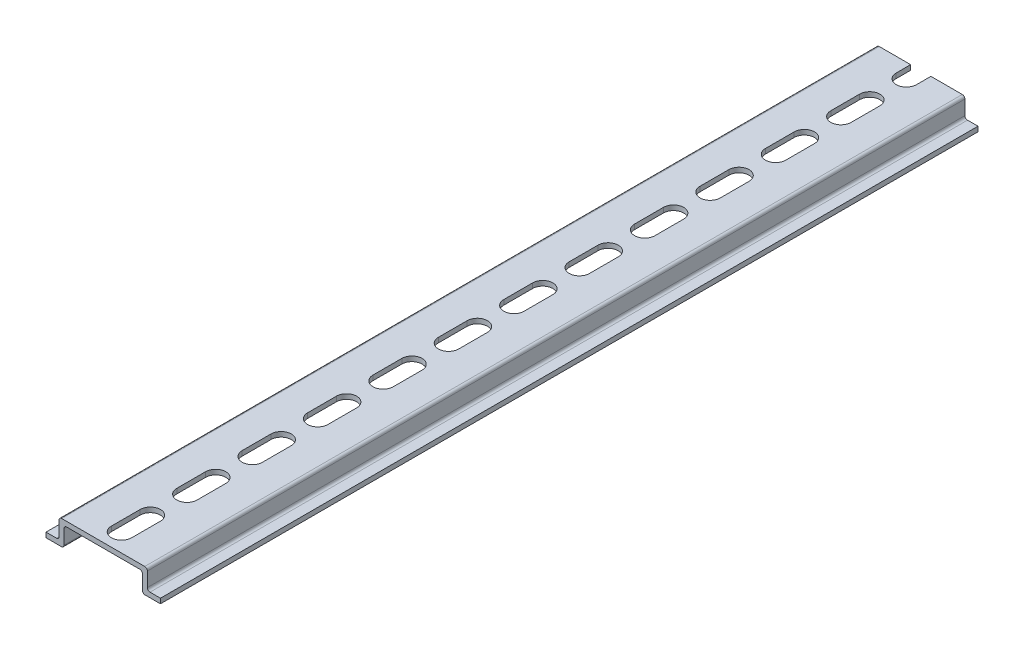
SolidWorks part; units mm, degrees
ref_plane "前视基准面" through (0, 0, 0) normal (0, 0, 1) x (1, 0, 0)
ref_plane "上视基准面" through (0, 0, 0) normal (0, 1, 0) x (1, 0, 0)
ref_plane "右视基准面" through (0, 0, 0) normal (1, 0, 0) x (0, 0, -1)
sketch "草图1" plane through (0, 0, 0) normal (0, 0, 1) x (1, 0, 0)
  line L0 (-17.5, 0) -> (-12.8, 0)
  line L1 (-12, 0.8) -> (-12, 5.2)
  line L2 (-11.2, 6) -> (11.2, 6)
  line L3 (12, 5.2) -> (12, 0.8)
  line L4 (12.8, 0) -> (17.5, 0)
  line L5 (13.5, 6.7) -> (13.5, 2.3)
  line L6 (12.7, 7.5) -> (-12.7, 7.5)
  line L7 (-13.5, 6.7) -> (-13.5, 2.3)
  line L8 (-14.3, 1.5) -> (-17.5, 1.5)
  line L9 (14.3, 1.5) -> (17.5, 1.5)
  line L10 (17.5, 1.5) -> (17.5, 0)
  line L11 (-17.5, 0) -> (-17.5, 1.5)
  line L12 (0, -9.8538) -> (0, 21.8077) construction
  arc A0 (12.7, 7.5) -> (13.5, 6.7) centre (12.7, 6.7) cw
  arc A1 (14.3, 1.5) -> (13.5, 2.3) centre (14.3, 2.3) cw
  arc A2 (12.8, 0) -> (12, 0.8) centre (12.8, 0.8) cw
  arc A3 (12, 5.2) -> (11.2, 6) centre (11.2, 5.2) ccw
  arc A4 (-12.8, 0) -> (-12, 0.8) centre (-12.8, 0.8) ccw
  arc A5 (-11.2, 6) -> (-12, 5.2) centre (-11.2, 5.2) ccw
  arc A6 (-13.5, 6.7) -> (-12.7, 7.5) centre (-12.7, 6.7) cw
  arc A7 (-13.5, 2.3) -> (-14.3, 1.5) centre (-14.3, 2.3) cw
  dimension "D6" = 0.8
  dimension "D1" = 1.5
  dimension "D2" = 7.5
  dimension "D3" = 35
  dimension "D4" = 1.5
  dimension "D5" = 1.5
  dimension "D7" = 27
extrude "凸台-拉伸1" add sketch "草图1" along normal blind 250
sketch "草图2" plane through (0, 0, 0) normal (0, 1, 0) x (1, 0, 0)
  line L0 (0, 22.1231) -> (0, -285.8608) construction
  line L1 (0, 4.4) -> (0, -4.4) construction
  line L2 (3.1, 4.4) -> (3.1, -4.4)
  line L3 (-3.1, 4.4) -> (-3.1, -4.4)
  line L4 (0, -15.6) -> (0, -24.4) construction
  line L5 (3.1, -15.6) -> (3.1, -24.4)
  line L6 (-3.1, -15.6) -> (-3.1, -24.4)
  line L7 (0, -35.6) -> (0, -44.4) construction
  line L8 (3.1, -35.6) -> (3.1, -44.4)
  line L9 (-3.1, -35.6) -> (-3.1, -44.4)
  line L10 (0, -55.6) -> (0, -64.4) construction
  line L11 (3.1, -55.6) -> (3.1, -64.4)
  line L12 (-3.1, -55.6) -> (-3.1, -64.4)
  line L13 (0, -75.6) -> (0, -84.4) construction
  line L14 (3.1, -75.6) -> (3.1, -84.4)
  line L15 (-3.1, -75.6) -> (-3.1, -84.4)
  line L16 (0, -95.6) -> (0, -104.4) construction
  line L17 (3.1, -95.6) -> (3.1, -104.4)
  line L18 (-3.1, -95.6) -> (-3.1, -104.4)
  line L19 (0, -115.6) -> (0, -124.4) construction
  line L20 (3.1, -115.6) -> (3.1, -124.4)
  line L21 (-3.1, -115.6) -> (-3.1, -124.4)
  line L22 (0, -135.6) -> (0, -144.4) construction
  line L23 (3.1, -135.6) -> (3.1, -144.4)
  line L24 (-3.1, -135.6) -> (-3.1, -144.4)
  line L25 (0, -155.6) -> (0, -164.4) construction
  line L26 (3.1, -155.6) -> (3.1, -164.4)
  line L27 (-3.1, -155.6) -> (-3.1, -164.4)
  line L28 (0, -175.6) -> (0, -184.4) construction
  line L29 (3.1, -175.6) -> (3.1, -184.4)
  line L30 (-3.1, -175.6) -> (-3.1, -184.4)
  line L31 (0, -195.6) -> (0, -204.4) construction
  line L32 (3.1, -195.6) -> (3.1, -204.4)
  line L33 (-3.1, -195.6) -> (-3.1, -204.4)
  line L34 (0, -215.6) -> (0, -224.4) construction
  line L35 (3.1, -215.6) -> (3.1, -224.4)
  line L36 (-3.1, -215.6) -> (-3.1, -224.4)
  line L37 (0, -235.6) -> (0, -244.4) construction
  line L38 (3.1, -235.6) -> (3.1, -244.4)
  line L39 (-3.1, -235.6) -> (-3.1, -244.4)
  arc A0 (3.1, 4.4) -> (-3.1, 4.4) centre (0, 4.4) ccw
  arc A1 (-3.1, -4.4) -> (3.1, -4.4) centre (0, -4.4) ccw
  arc A2 (3.1, -15.6) -> (-3.1, -15.6) centre (0, -15.6) ccw
  arc A3 (-3.1, -24.4) -> (3.1, -24.4) centre (0, -24.4) ccw
  arc A4 (3.1, -35.6) -> (-3.1, -35.6) centre (0, -35.6) ccw
  arc A5 (-3.1, -44.4) -> (3.1, -44.4) centre (0, -44.4) ccw
  arc A6 (3.1, -55.6) -> (-3.1, -55.6) centre (0, -55.6) ccw
  arc A7 (-3.1, -64.4) -> (3.1, -64.4) centre (0, -64.4) ccw
  arc A8 (3.1, -75.6) -> (-3.1, -75.6) centre (0, -75.6) ccw
  arc A9 (-3.1, -84.4) -> (3.1, -84.4) centre (0, -84.4) ccw
  arc A10 (3.1, -95.6) -> (-3.1, -95.6) centre (0, -95.6) ccw
  arc A11 (-3.1, -104.4) -> (3.1, -104.4) centre (0, -104.4) ccw
  arc A12 (3.1, -115.6) -> (-3.1, -115.6) centre (0, -115.6) ccw
  arc A13 (-3.1, -124.4) -> (3.1, -124.4) centre (0, -124.4) ccw
  arc A14 (3.1, -135.6) -> (-3.1, -135.6) centre (0, -135.6) ccw
  arc A15 (-3.1, -144.4) -> (3.1, -144.4) centre (0, -144.4) ccw
  arc A16 (3.1, -155.6) -> (-3.1, -155.6) centre (0, -155.6) ccw
  arc A17 (-3.1, -164.4) -> (3.1, -164.4) centre (0, -164.4) ccw
  arc A18 (3.1, -175.6) -> (-3.1, -175.6) centre (0, -175.6) ccw
  arc A19 (-3.1, -184.4) -> (3.1, -184.4) centre (0, -184.4) ccw
  arc A20 (3.1, -195.6) -> (-3.1, -195.6) centre (0, -195.6) ccw
  arc A21 (-3.1, -204.4) -> (3.1, -204.4) centre (0, -204.4) ccw
  arc A22 (3.1, -215.6) -> (-3.1, -215.6) centre (0, -215.6) ccw
  arc A23 (-3.1, -224.4) -> (3.1, -224.4) centre (0, -224.4) ccw
  arc A24 (3.1, -235.6) -> (-3.1, -235.6) centre (0, -235.6) ccw
  arc A25 (-3.1, -244.4) -> (3.1, -244.4) centre (0, -244.4) ccw
  point P5 (0, 0)
  point P10 (0, 7.5)
  point P11 (0, -7.5)
  point P16 (0, -20)
  point P23 (0, -40)
  point P30 (0, -60)
  point P37 (0, -80)
  point P44 (0, -100)
  point P51 (0, -120)
  point P58 (0, -140)
  point P65 (0, -160)
  point P72 (0, -180)
  point P79 (0, -200)
  point P86 (0, -220)
  point P93 (0, -240)
  dimension "D1" = 15
  dimension "D2" = 6.2
  dimension "D3" = 13
extrude "切除-拉伸2" cut sketch "草图2" along normal up to surface (7.5 mm away) up to face at (0, 7.5, 125)
